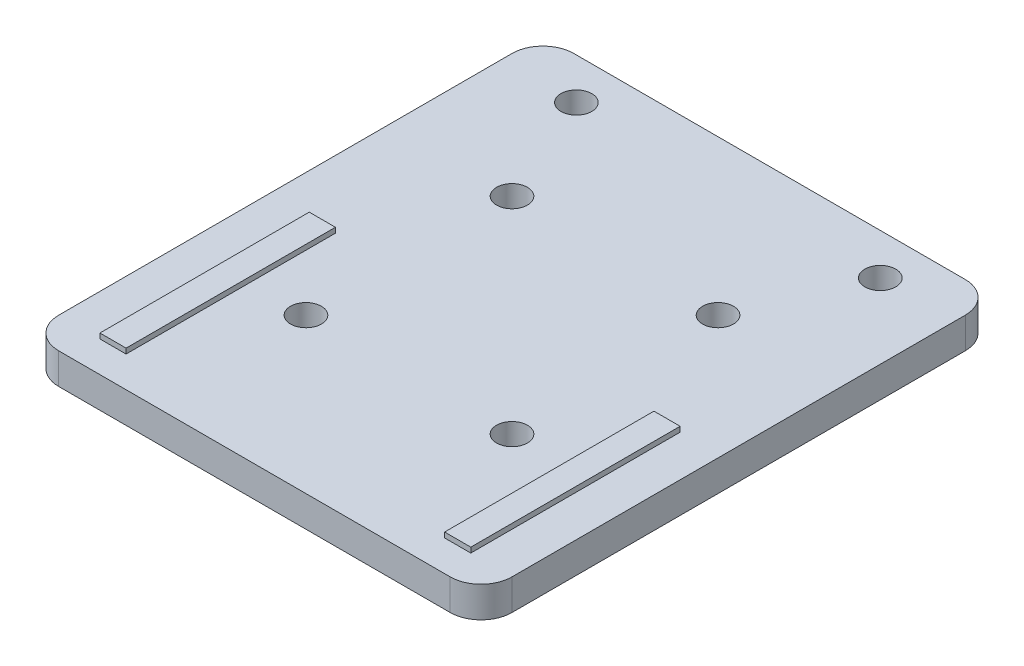
SolidWorks part; units mm, degrees
ref_plane "前视基准面" through (0, 0, 0) normal (0, 0, 1) x (1, 0, 0)
ref_plane "上视基准面" through (0, 0, 0) normal (0, 1, 0) x (1, 0, 0)
ref_plane "右视基准面" through (0, 0, 0) normal (1, 0, 0) x (0, 0, -1)
other "Configuration Table"
sketch "草图1" plane through (0, 0, 0) normal (0, 1, 0) x (1, 0, 0)
  line L0 (0, 0) -> (31.4714, 0) construction
  line L1 (-22, -25) -> (22, -25)
  line L2 (-22, -25) -> (-22, 25)
  line L3 (-22, 25) -> (22, 25)
  line L4 (22, -25) -> (22, 25)
  line L5 (-22, -25) -> (22, 25) construction
  line L6 (-22, 25) -> (22, -25) construction
  line L7 (0, 0) -> (0, 29.2234) construction
  circle A0 centre (-10, 10) radius 1.5
  circle A2 centre (10, 10) radius 1.5
  circle A3 centre (10, -10) radius 1.5
  circle A4 centre (-10, -10) radius 1.5
  circle A5 centre (-14.75, 21) radius 1.5
  circle A6 centre (14.75, 21) radius 1.5
  point P0 (0, 0)
  dimension "D3" = 3
  dimension "D4" = 20
  dimension "D5" = 20
  dimension "D6" = 3
  dimension "D7" = 29.5
  dimension "D1" = 44
  dimension "D2" = 50
  dimension "D8" = 4
extrude "凸台-拉伸1" add sketch "草图1" along normal blind 3
fillet "圆角1" radius 3 4 edges at (-22, 1.5, -25) (-22, 1.5, 25) (22, 1.5, -25) (22, 1.5, 25)
sketch "草图2" plane through (0, 3, 0) normal (0, 1, 0) x (1, 0, 0)
  line L0 (0, -25) -> (0, 26.3697) construction
  line L1 (-19, -25) -> (19, -25) construction
  line L2 (-15.46, -22) -> (-15.46, -1.68)
  line L3 (-15.46, -1.68) -> (-18, -1.68)
  line L4 (-18, -1.68) -> (-18, -22)
  line L5 (-18, -22) -> (-15.46, -22)
  line L6 (18, -1.68) -> (18, -22)
  line L7 (15.46, -1.68) -> (18, -1.68)
  line L8 (15.46, -22) -> (15.46, -1.68)
  line L9 (18, -22) -> (15.46, -22)
  dimension "D1" = 2.54
  dimension "D2" = 20.32
  dimension "D3" = 30.92
  dimension "D4" = 3
extrude "凸台-拉伸2" add sketch "草图2" along normal blind 0.5
